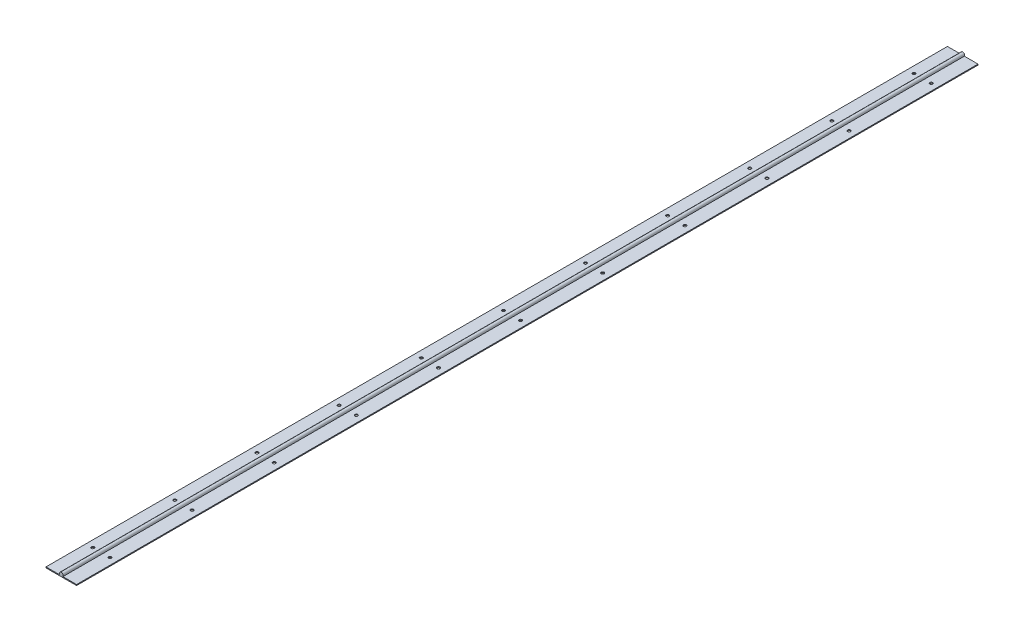
SolidWorks part; units mm, degrees
ref_plane "front" through (0, 0, 0) normal (0, 0, 1) x (1, 0, 0)
ref_plane "top" through (0, 0, 0) normal (0, 1, 0) x (1, 0, 0)
ref_plane "right" through (0, 0, 0) normal (1, 0, 0) x (0, 0, -1)
sketch "Sketch1" plane through (0, 0, 0) normal (0, 0, 1) x (1, 0, 0)
  line L0 (-25.4, 0) -> (25.4, 0)
  line L1 (25.4, 0) -> (25.4, 1.524)
  line L2 (25.4, 1.524) -> (2.712, 1.524)
  line L3 (-2.712, 1.524) -> (-25.4, 1.524)
  line L4 (-25.4, 1.524) -> (-25.4, 0)
  arc A0 (2.712, 1.524) -> (-2.712, 1.524) centre (0, 3.175) ccw
  dimension "D1" = 3.175
  dimension "D2" = 1.524
  dimension "D3" = 50.8
extrude "Extrude1" add sketch "Sketch1" against normal blind 1498.6
sketch "Sketch2" plane through (0, 0, 0) normal (0, 1, 0) x (1, 0, 0)
  circle A0 centre (14.3002, 66.675) radius 2.4257
  circle A1 centre (-14.3002, 66.675) radius 2.4257
  dimension "D3" = 4.8514
  dimension "D1" = 14.3002
  dimension "D2" = 66.675
  dimension "D4" = 14.3002
extrude "Cut-Extrude1" cut sketch "Sketch2" along normal through all
pattern_linear "LPattern1" count 11 spacing 136.525 along (0, 0, -1) of "Cut-Extrude1"
